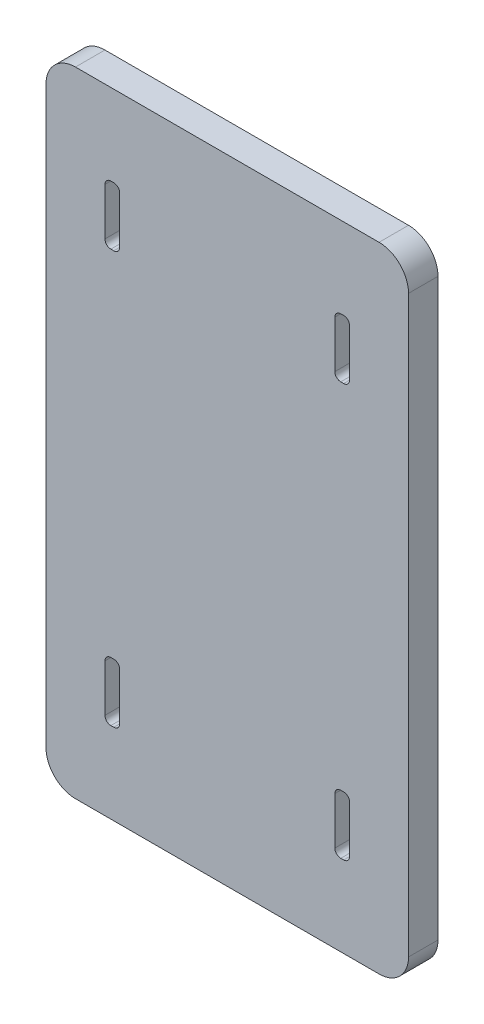
SolidWorks part; units mm, degrees
ref_plane "Front Plane" through (0, 0, 0) normal (0, 0, 1) x (1, 0, 0)
ref_plane "Top Plane" through (0, 0, 0) normal (0, 1, 0) x (1, 0, 0)
ref_plane "Right Plane" through (0, 0, 0) normal (1, 0, 0) x (0, 0, -1)
sketch "Croquis2" plane through (0, 0, 0) normal (0, 0, 1) x (1, 0, 0)
  line L0 (-576.7146, 1109.0214) -> (-576.7146, 894.0214) construction
  line L1 (-628.2146, 894.0214) -> (-525.2146, 894.0214)
  line L2 (-638.2146, 904.0214) -> (-638.2146, 1099.0214)
  line L3 (-628.2146, 1109.0214) -> (-525.2146, 1109.0214)
  line L4 (-515.2146, 904.0214) -> (-515.2146, 1099.0214)
  line L5 (-638.2146, 894.0214) -> (-515.2146, 1109.0214) construction
  line L6 (-638.2146, 1109.0214) -> (-515.2146, 894.0214) construction
  line L7 (-576.7146, 1001.5214) -> (-515.2146, 1001.5214) construction
  line L12 (-537.2146, 1081.5214) -> (-538.2146, 1081.5214)
  line L13 (-540.2146, 1063.5214) -> (-540.2146, 1079.5214)
  line L14 (-616.2146, 1061.5214) -> (-615.2146, 1061.5214)
  line L15 (-618.2146, 1063.5214) -> (-618.2146, 1079.5214)
  line L16 (-616.2146, 1081.5214) -> (-615.2146, 1081.5214)
  line L17 (-613.2146, 1063.5214) -> (-613.2146, 1079.5214)
  line L18 (-618.2146, 1061.5214) -> (-613.2146, 1081.5214) construction
  line L19 (-618.2146, 1081.5214) -> (-613.2146, 1061.5214) construction
  line L20 (-537.2146, 1061.5214) -> (-538.2146, 1061.5214)
  line L21 (-535.2146, 1063.5214) -> (-535.2146, 1079.5214)
  line L22 (-535.2146, 939.5214) -> (-535.2146, 923.5214)
  line L23 (-537.2146, 941.5214) -> (-538.2146, 941.5214)
  line L24 (-540.2146, 939.5214) -> (-540.2146, 923.5214)
  line L25 (-537.2146, 921.5214) -> (-538.2146, 921.5214)
  line L26 (-616.2146, 921.5214) -> (-615.2146, 921.5214)
  line L27 (-613.2146, 939.5214) -> (-613.2146, 923.5214)
  line L28 (-616.2146, 941.5214) -> (-615.2146, 941.5214)
  line L29 (-618.2146, 939.5214) -> (-618.2146, 923.5214)
  arc A0 (-638.2146, 1099.0214) -> (-628.2146, 1109.0214) centre (-628.2146, 1099.0214) cw
  arc A1 (-628.2146, 894.0214) -> (-638.2146, 904.0214) centre (-628.2146, 904.0214) cw
  arc A2 (-525.2146, 894.0214) -> (-515.2146, 904.0214) centre (-525.2146, 904.0214) ccw
  arc A3 (-515.2146, 1099.0214) -> (-525.2146, 1109.0214) centre (-525.2146, 1099.0214) ccw
  arc A4 (-615.2146, 1061.5214) -> (-613.2146, 1063.5214) centre (-615.2146, 1063.5214) ccw
  arc A5 (-616.2146, 1061.5214) -> (-618.2146, 1063.5214) centre (-616.2146, 1063.5214) cw
  arc A6 (-615.2146, 1081.5214) -> (-613.2146, 1079.5214) centre (-615.2146, 1079.5214) cw
  arc A7 (-618.2146, 1079.5214) -> (-616.2146, 1081.5214) centre (-616.2146, 1079.5214) cw
  arc A8 (-538.2146, 1081.5214) -> (-540.2146, 1079.5214) centre (-538.2146, 1079.5214) ccw
  arc A9 (-538.2146, 1061.5214) -> (-540.2146, 1063.5214) centre (-538.2146, 1063.5214) cw
  arc A10 (-537.2146, 1061.5214) -> (-535.2146, 1063.5214) centre (-537.2146, 1063.5214) ccw
  arc A11 (-535.2146, 1079.5214) -> (-537.2146, 1081.5214) centre (-537.2146, 1079.5214) ccw
  arc A12 (-535.2146, 923.5214) -> (-537.2146, 921.5214) centre (-537.2146, 923.5214) cw
  arc A13 (-537.2146, 941.5214) -> (-535.2146, 939.5214) centre (-537.2146, 939.5214) cw
  arc A14 (-538.2146, 941.5214) -> (-540.2146, 939.5214) centre (-538.2146, 939.5214) ccw
  arc A15 (-538.2146, 921.5214) -> (-540.2146, 923.5214) centre (-538.2146, 923.5214) cw
  arc A16 (-615.2146, 921.5214) -> (-613.2146, 923.5214) centre (-615.2146, 923.5214) ccw
  arc A17 (-615.2146, 941.5214) -> (-613.2146, 939.5214) centre (-615.2146, 939.5214) cw
  arc A18 (-616.2146, 941.5214) -> (-618.2146, 939.5214) centre (-616.2146, 939.5214) ccw
  arc A19 (-618.2146, 923.5214) -> (-616.2146, 921.5214) centre (-616.2146, 923.5214) ccw
  point P0 (-576.7146, 1001.5214)
  point P19 (-612.6316, 963.6562)
  point P24 (-615.7146, 1071.5214)
  dimension "D3" = 10
  dimension "D7" = 2
  dimension "D1" = 123
  dimension "D2" = 215
  dimension "D4" = 5
  dimension "D5" = 20
  dimension "D6" = 39
  dimension "D8" = 70
extrude "Saliente-Extruir1" add sketch "Croquis2" along normal blind 10
